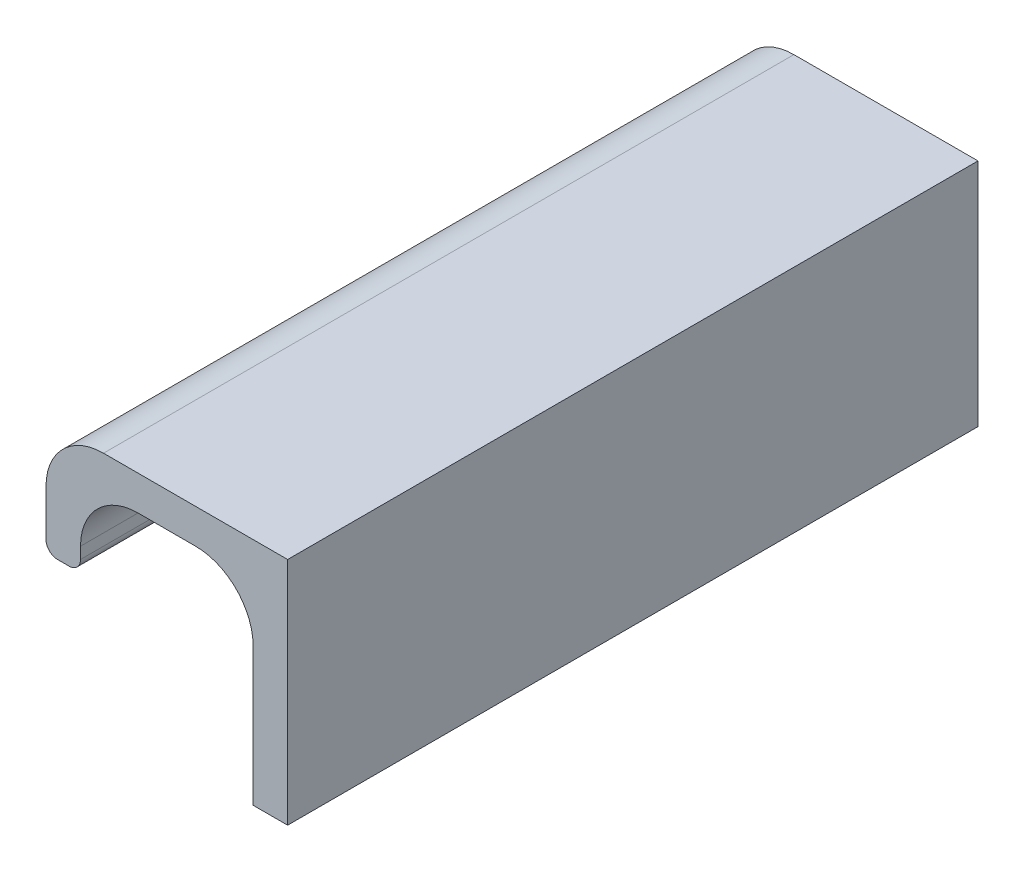
SolidWorks part; units mm, degrees
ref_plane "Front Plane" through (0, 0, 0) normal (0, 0, 1) x (1, 0, 0)
ref_plane "Top Plane" through (0, 0, 0) normal (0, 1, 0) x (1, 0, 0)
ref_plane "Right Plane" through (0, 0, 0) normal (1, 0, 0) x (0, 0, -1)
sketch "Sketch1" plane through (0, 0, 0) normal (0, 0, 1) x (1, 0, 0)
  line L0 (0, 0) -> (0, -62.0657) construction
  line L1 (0, 0) -> (0, -20)
  line L2 (0, -20) -> (-3, -20)
  line L3 (-3, -20) -> (-3, -8)
  line L4 (-8, -3) -> (-13, -3)
  line L5 (-18, -8) -> (-18, -9)
  line L6 (-19, -10) -> (-20, -10)
  line L7 (-21, -9) -> (-21, -5)
  line L8 (-16, 0) -> (0, 0)
  arc A0 (-3, -8) -> (-8, -3) centre (-8, -8) ccw
  arc A1 (-21, -5) -> (-16, 0) centre (-16, -5) cw
  arc A2 (-13, -3) -> (-18, -8) centre (-13, -8) ccw
  arc A3 (-18, -9) -> (-19, -10) centre (-19, -9) cw
  arc A4 (-20, -10) -> (-21, -9) centre (-20, -9) cw
  point P12 (-3, -3)
  point P15 (-21, 0)
  point P18 (-18, -3)
  point P21 (-18, -10)
  point P24 (-21, -10)
  dimension "D7" = 5
  dimension "D8" = 1
  dimension "D1" = 20
  dimension "D2" = 3
  dimension "D3" = 15
  dimension "D4" = 3
  dimension "D5" = 3
  dimension "D6" = 10
extrude "Boss-Extrude1" add sketch "Sketch1" along normal blind 60
